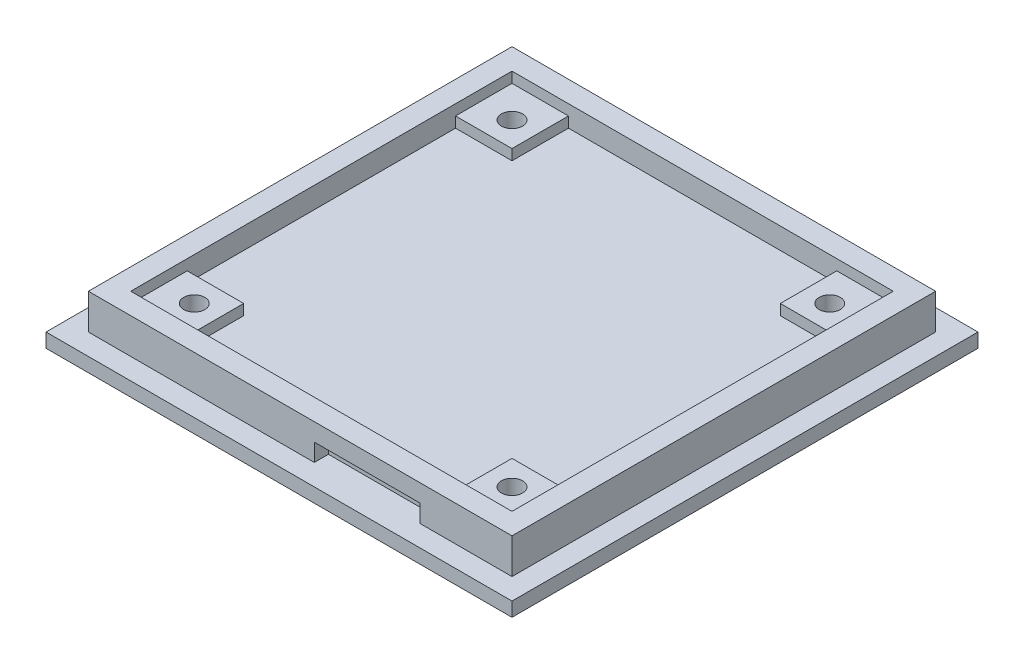
SolidWorks part; units mm, degrees
ref_plane "Front Plane" through (0, 0, 0) normal (0, 0, 1) x (1, 0, 0)
ref_plane "Top Plane" through (0, 0, 0) normal (0, 1, 0) x (1, 0, 0)
ref_plane "Right Plane" through (0, 0, 0) normal (1, 0, 0) x (0, 0, -1)
sketch "Sketch1" plane through (0, 0, 0) normal (0, 1, 0) x (1, 0, 0)
  line L0 (0, -55) -> (0, 55) construction
  line L1 (-30, 30) -> (30, 30)
  line L2 (-30, 30) -> (-30, -30)
  line L3 (-30, -30) -> (30, -30)
  line L4 (30, 30) -> (30, -30)
  line L5 (-55, 0) -> (55, 0) construction
  dimension "D1" = 30
  dimension "D2" = 60
  dimension "D3" = 60
  dimension "D4" = 30
extrude "Boss-Extrude1" add sketch "Sketch1" along normal blind 5
sketch "Sketch2" plane through (0, 5, 0) normal (0, 1, 0) x (1, 0, 0)
  line L1 (-27, 27) -> (27, 27)
  line L2 (-27, 27) -> (-27, -27)
  line L3 (-27, -27) -> (27, -27)
  line L4 (27, 27) -> (27, -27)
  line L5 (-30, 30) -> (-30, -30) construction
  line L6 (30, 30) -> (-30, 30) construction
  line L7 (30, -30) -> (30, 30) construction
  line L8 (-30, -30) -> (30, -30) construction
  dimension "D1" = 3
  dimension "D2" = 3
  dimension "D3" = 3
  dimension "D4" = 3
extrude "Cut-Extrude1" cut sketch "Sketch2" against normal blind 3
sketch "Sketch5" plane through (0, 0, 30) normal (0, 0, -1) x (-1, 0, 0)
  line L0 (33, 0) -> (-33, 0) construction
  line L1 (-17, 2.5) -> (-2, 2.5)
  line L2 (-17, 2.5) -> (-17, 0)
  line L3 (-17, 0) -> (-2, 0)
  line L4 (-2, 2.5) -> (-2, 0)
  line L5 (-30, 5) -> (-30, 0) construction
  dimension "D1" = 13
  dimension "D2" = 15
  dimension "D3" = 2.5
extrude "Cut-Extrude3" cut sketch "Sketch5" along normal blind 2
sketch "Sketch6" plane through (0, 0, -30) normal (0, 0, -1) x (-1, 0, 0)
  line L0 (-30, 0) -> (30, 0) construction
  line L1 (-23.5, 0) -> (-11.5, 0)
  line L2 (-23.5, 0) -> (-23.5, 2)
  line L3 (-23.5, 2) -> (-11.5, 2)
  line L4 (-11.5, 0) -> (-11.5, 2)
  line L5 (-30, 5) -> (-30, 0) construction
  dimension "D1" = 6.5
  dimension "D2" = 12
  dimension "D3" = 2
extrude "Cut-Extrude4" cut sketch "Sketch6" against normal blind 2
sketch "Sketch7" plane through (0, 0, 0) normal (0, -1, 0) x (1, 0, 0)
  line L0 (-30, -30) -> (-30, 30) construction
  line L1 (-33, 33) -> (33, 33)
  line L2 (-33, 33) -> (-33, -33)
  line L3 (-33, -33) -> (33, -33)
  line L4 (33, 33) -> (33, -33)
  line L5 (-30, 30) -> (2, 30) construction
  line L6 (30, 30) -> (30, -30) construction
  line L7 (11.5, -30) -> (23.5, -30) construction
  dimension "D1" = 3
  dimension "D2" = 3
  dimension "D3" = 3
  dimension "D4" = 3
extrude "Boss-Extrude3" add sketch "Sketch7" along normal blind 2
sketch "Sketch4" plane through (0, 2, 0) normal (0, 1, 0) x (1, 0, 0)
  line L0 (27, 19) -> (19, 19)
  line L1 (-19, 19) -> (-27, 19)
  line L2 (-19, 19) -> (-19, 27)
  line L3 (-19, 27) -> (-27, 27)
  line L4 (-27, 19) -> (-27, 27)
  line L5 (27, 19) -> (27, 27)
  line L6 (27, 27) -> (19, 27)
  line L7 (19, 19) -> (19, 27)
  line L8 (27, -27) -> (19, -27)
  line L9 (27, -27) -> (27, -19)
  line L10 (27, -19) -> (19, -19)
  line L11 (19, -27) -> (19, -19)
  line L12 (-19, -27) -> (-27, -27)
  line L13 (-19, -27) -> (-19, -19)
  line L14 (-19, -19) -> (-27, -19)
  line L15 (-27, -27) -> (-27, -19)
  dimension "D1" = 8
  dimension "D2" = 8
  dimension "D3" = 2
  dimension "D4" = 2
extrude "Boss-Extrude2" add sketch "Sketch4" along normal blind 1.5
sketch "Sketch3" plane through (0, 3.5, 0) normal (0, 1, 0) x (1, 0, 0)
  line L1 (19, 27) -> (-19, 27) construction
  line L2 (-27, 27) -> (-27, -27) construction
  circle A0 centre (-22.5, 22.5) radius 1.5
  circle A1 centre (22.5, 22.5) radius 1.5
  circle A2 centre (22.5, -22.5) radius 1.5
  circle A3 centre (-22.5, -22.5) radius 1.5
  dimension "D1" = 4.5
  dimension "D2" = 4.5
  dimension "D3" = 2
  dimension "D4" = 2
extrude "Cut-Extrude2" cut sketch "Sketch3" against normal up to surface (5.5 mm away) up to face at (0, -2, 0)
